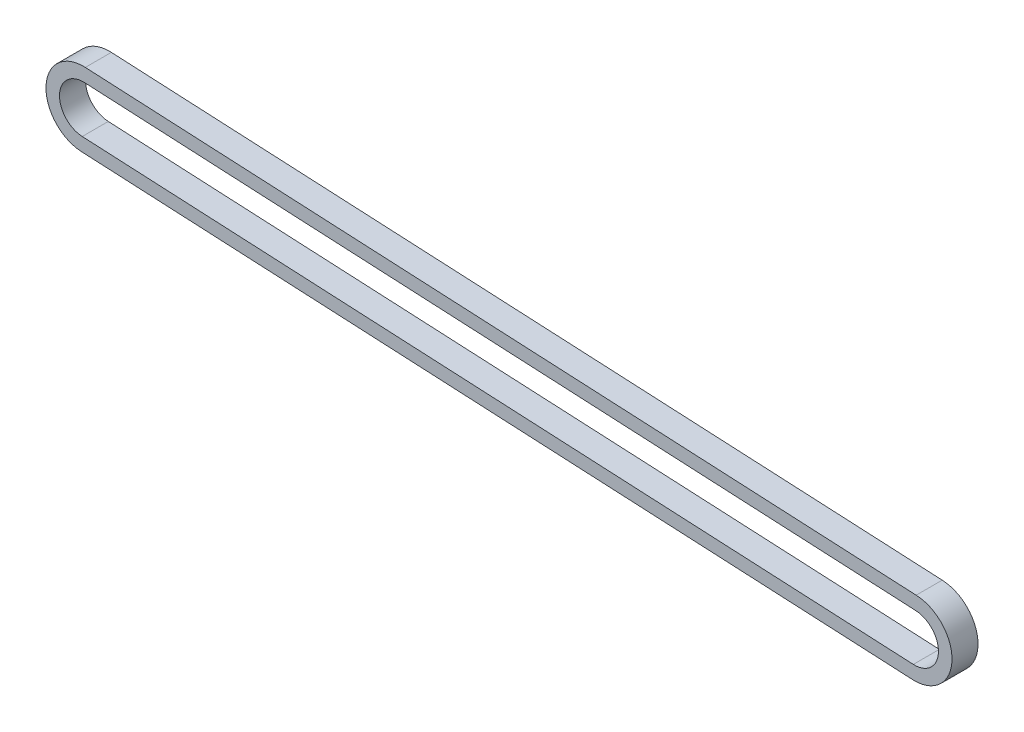
SolidWorks part; units mm, degrees
ref_plane "Front Plane" through (0, 0, 0) normal (0, 0, 1) x (1, 0, 0)
ref_plane "Top Plane" through (0, 0, 0) normal (0, 1, 0) x (1, 0, 0)
ref_plane "Right Plane" through (0, 0, 0) normal (1, 0, 0) x (0, 0, -1)
sketch "Sketch1" plane through (0, 0, 0) normal (0, 0, 1) x (1, 0, 0)
  line L2 (-101.4922, 2.1627) -> (-0.1462, -2.9173)
  line L3 (0.124, 2.9184) -> (-101.1998, 7.9973)
  line L6 (0.2011, 4.5676) -> (-101.1171, 9.6463)
  line L7 (-101.5749, 0.5137) -> (-0.2289, -4.5663)
  circle A0 centre (0, 0) radius 2.921 construction
  circle A1 centre (-101.346, 5.08) radius 2.921 construction
  arc A4 (-0.1462, -2.9173) -> (0.124, 2.9184) centre (0, 0) ccw
  arc A5 (-101.1998, 7.9973) -> (-101.4922, 2.1627) centre (-101.346, 5.08) ccw
  arc A8 (-101.1171, 9.6463) -> (-101.5749, 0.5137) centre (-101.346, 5.08) ccw
  arc A9 (-0.2289, -4.5663) -> (0.2011, 4.5676) centre (0, 0) ccw
  dimension "D1" = 5.842
  dimension "D2" = 5.842
  dimension "D5" = 221.2997
  dimension "D6" = 231.6732
  dimension "D3" = 101.346
  dimension "D4" = 5.08
  dimension "D8" = 1.651
extrude "Boss-Extrude1" add sketch "Sketch1" along normal blind 3.175
